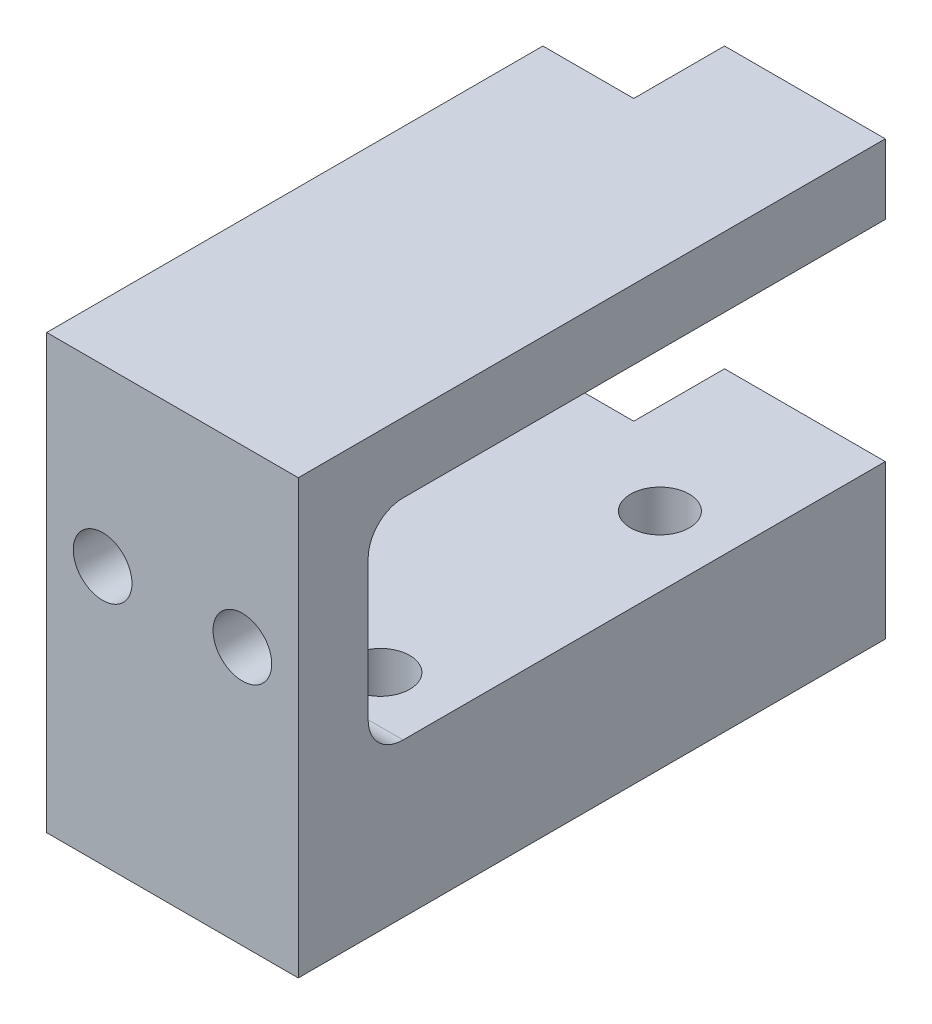
SolidWorks part; units mm, degrees
material "1060 Alloy"
ref_plane "Front Plane" through (0, 0, 0) normal (0, 0, 1) x (1, 0, 0)
ref_plane "Top Plane" through (0, 0, 0) normal (0, 1, 0) x (1, 0, 0)
ref_plane "Right Plane" through (0, 0, 0) normal (1, 0, 0) x (0, 0, -1)
sketch "Sketch1" plane through (0, 0, 0) normal (0, 0, 1) x (1, 0, 0)
  line L1 (-9, -10) -> (9, -10)
  line L2 (-9, -10) -> (-9, 10)
  line L3 (-9, 10) -> (9, 10)
  line L4 (9, -10) -> (9, 10)
  line L5 (-9, -10) -> (9, 10) construction
  line L6 (-9, 10) -> (9, -10) construction
  point P0 (0, 0)
  dimension "D1" = 20
  dimension "D2" = 18
extrude "Boss-Extrude1" add sketch "Sketch1" along normal mid plane 5
sketch "Sketch2" plane through (0, 0, 2.5) normal (0, 0, -1) x (-1, 0, 0)
  line L1 (9, -10) -> (-9, -10)
  line L2 (9, -10) -> (9, -5)
  line L3 (9, -5) -> (-9, -5)
  line L4 (-9, -10) -> (-9, -5)
  line L5 (9, -10) -> (-9, -5) construction
  line L6 (9, -5) -> (-9, -10) construction
  line L7 (9, 10) -> (9, -10) construction
  point P4 (0, -7.5)
  dimension "D1" = 5
extrude "Boss-Extrude2" add sketch "Sketch2" along normal blind 42
sketch "Sketch7" plane through (0, 0, 2.5) normal (0, 0, 1) x (1, 0, 0)
  line L0 (-9, 10) -> (-9, -10) construction
  line L1 (-9, 10) -> (9, 10)
  line L2 (-9, 10) -> (-9, 15)
  line L3 (-9, 15) -> (9, 15)
  line L4 (9, 10) -> (9, 15)
  line L5 (-9, 10) -> (9, 15) construction
  line L6 (-9, 15) -> (9, 10) construction
  line L7 (9, -10) -> (9, 10) construction
  line L9 (9, 10) -> (-9, 10) construction
  point P4 (0, 12.5)
  dimension "D2" = 5
extrude "Boss-Extrude3" add sketch "Sketch7" against normal up to surface (42 mm away) up to face at (0, -7.5, -39.5)
hole_wizard "CSK for M3 Hex Socket Countersunk Cap Screw1" positions "Sketch3" profile "Sketch4" hole size "M4" standard "ISO" end condition through all
sketch "Sketch3" plane through (0, 0, 2.5) normal (0, 0, 1) x (1, 0, 0)
  point P0 (-5, 2.5)
  point P3 (5, 2.5)
sketch "Sketch4" plane through (-5, 2.5, 2.5) normal (1, 0, 0) x (0, -1, 0)
  line L0 (0, 0) -> (0, 42)
  line L1 (0, 42) -> (2.1, 42)
  line L2 (2.1, 42) -> (2.1, 0)
  line L5 (2.1, 0) -> (0, 0)
  line L11 (0, -6.35) -> (0, 107.95) construction
  dimension "Thru Hole Dia." = 4.2
  dimension "Thru Hole Depth" = 42
sketch "Sketch10" plane through (0, -10, 0) normal (0, -1, 0) x (1, 0, 0)
  line L1 (9, 2.5) -> (-9, 2.5)
  line L2 (9, 2.5) -> (9, -39.5)
  line L3 (9, -39.5) -> (-9, -39.5)
  line L4 (-9, 2.5) -> (-9, -39.5)
  line L5 (9, 2.5) -> (-9, -39.5) construction
  line L6 (9, -39.5) -> (-9, 2.5) construction
  point P4 (0, -18.5)
extrude "Boss-Extrude4" add sketch "Sketch10" along normal blind 6
sketch "Sketch9" plane through (0, -16, 0) normal (0, -1, 0) x (1, 0, 0)
  line L1 (-9, -39.5) -> (-2.5, -39.5)
  line L2 (-9, -39.5) -> (-9, -33)
  line L3 (-9, -33) -> (-2.5, -33)
  line L4 (-2.5, -39.5) -> (-2.5, -33)
  line L5 (-9, -39.5) -> (-2.5, -33) construction
  line L6 (-9, -33) -> (-2.5, -39.5) construction
  point P4 (-5.75, -36.25)
  dimension "D1" = 6.5
  dimension "D2" = 6.5
extrude "Cut-Extrude2" cut sketch "Sketch9" against normal through all
hole_wizard "Tapped Hole for M4x0.7 Helicoil1" positions "Sketch5" profile "Sketch6" tap size "M4x0.7" standard "Helicoil® Metric"
sketch "Sketch5" plane through (0, -16, 0) normal (0, -1, 0) x (-1, 0, 0)
  line L10 (-4, 30.475) -> (-4, 26.275) construction
  line L12 (-9, 39.5) -> (-9, -2.5) construction
  line L13 (-4, 10.475) -> (-4, 6.275) construction
  point P31 (-4, 28.375)
  point P60 (-4, 8.375)
  dimension "D2" = 5
sketch "Sketch6" plane through (4, -16, -28.375) normal (1, 0, 0) x (0, 0, -1)
  line L0 (0, 0) -> (0, 11)
  line L1 (0, 11) -> (2.1, 11)
  line L2 (2.1, 11) -> (2.1, 0)
  line L5 (2.1, 0) -> (0, 0)
  line L11 (0, -6.35) -> (0, 107.95) construction
  dimension "Thru Tap Drill Dia." = 4.2
  dimension "Thru Tap Drill Depth" = 11
cosmetic thread "Hole Thread5" parameters "D1"=7.2, "D2"=5.007
cosmetic thread "Hole Thread6" parameters "D1"=7.2, "D2"=5.007
sketch "Sketch11" plane through (0, -16, 0) normal (0, -1, 0) x (-1, 0, 0)
  line L0 (9, -2.5) -> (9, 33) construction
  circle A0 centre (4, 8.375) radius 2
  dimension "D2" = 4
  dimension "D1" = 5
extrude "Cut-Extrude3" cut sketch "Sketch11" against normal blind 6
fillet "Fillet1" radius 2.5 2 edges at (0, -5, -2.5) (0, 10, -2.5)
